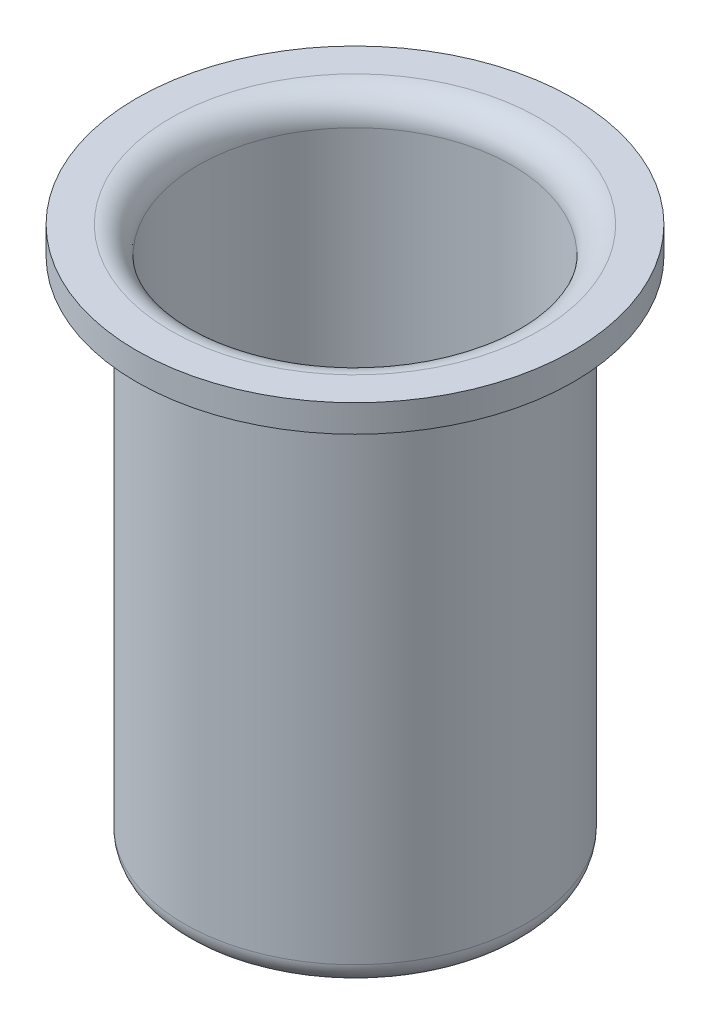
SolidWorks part; units mm, degrees
material "Glass"
ref_plane "Front" through (0, 0, 0) normal (0, 0, 1) x (1, 0, 0)
ref_plane "Top" through (0, 0, 0) normal (0, 1, 0) x (1, 0, 0)
ref_plane "Right" through (0, 0, 0) normal (1, 0, 0) x (0, 0, -1)
sketch "Sketch1" plane through (0, 0, 0) normal (0, 0, 1) x (1, 0, 0)
  line L0 (0, 0) -> (0, 159) construction
  line L1 (50, 151) -> (50, 6.5)
  line L2 (0, 0) -> (43.5, 0)
  line L3 (50, 151) -> (64, 151)
  line L4 (64, 151) -> (64, 159)
  line L5 (64, 159) -> (46, 159)
  line L6 (46, 159) -> (46, 6.5)
  line L7 (43.5, 4) -> (0, 4)
  line L8 (0, 4) -> (0, 0)
  arc A0 (43.5, 0) -> (50, 6.5) centre (43.5, 6.5) ccw
  arc A1 (46, 6.5) -> (43.5, 4) centre (43.5, 6.5) cw
  point P8 (0, 0)
  point P13 (0, 0)
  dimension "D6" = 6.5
  dimension "D1" = 4
  dimension "D2" = 100
  dimension "D3" = 155
  dimension "D4" = 8
  dimension "D5" = 14
revolve "Revolve1" add sketch "Sketch1" angle 360 about L0
fillet "Fillet1" radius 4 1 edges at (0, 151, -50)
fillet "Fillet2" radius 8 1 edges at (0, 159, -46)
